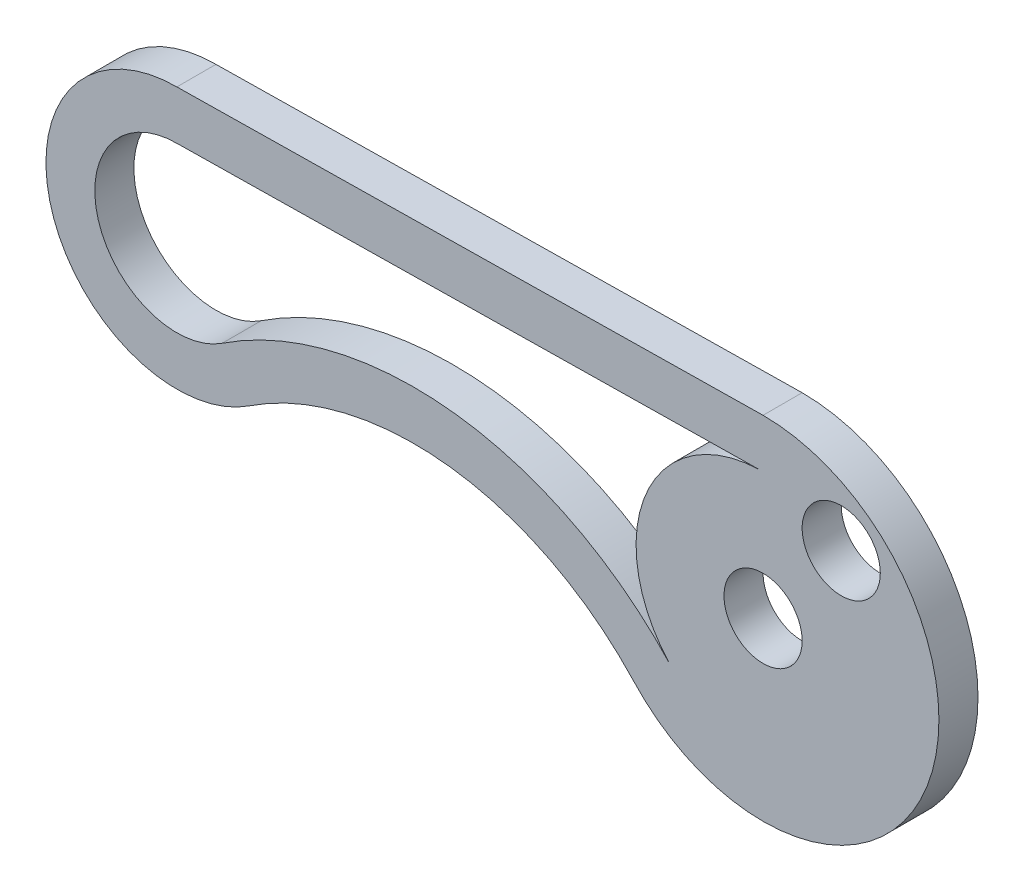
SolidWorks part; units mm, degrees
ref_plane "Front Plane" through (0, 0, 0) normal (0, 0, 1) x (1, 0, 0)
ref_plane "Top Plane" through (0, 0, 0) normal (0, 1, 0) x (1, 0, 0)
ref_plane "Right Plane" through (0, 0, 0) normal (1, 0, 0) x (0, 0, -1)
sketch "Sketch1" plane through (0, 0, 0) normal (0, 0, 1) x (1, 0, 0)
  line L0 (-31.0207, 8.8289) -> (-1.0207, 9.2757)
  line L1 (-31.0042, 6.3289) -> (-1.2314, 6.7723)
  line L3 (-31.0042, 6.3289) -> (-0.9835, 6.776) construction
  arc A0 (-31.0207, 8.8289) -> (-27.3206, -3.4568) centre (-31.0207, 2.1289) ccw
  arc A1 (-7.632, -5.8309) -> (-1.2887, 9.2717) centre (-1.0207, 0.2757) ccw
  arc A2 (-7.632, -5.8309) -> (-27.3206, -3.4568) centre (-18.8713, -16.2121) ccw
  circle A4 centre (-1.0207, 0.2757) radius 2
  circle A5 centre (2.9793, 5.2757) radius 2
  arc A6 (2.1739, 3.4451) -> (1.3701, 4.0881) centre (-1.0207, 0.2757) ccw
  arc A8 (-5.7955, -4.1346) -> (-28.7013, -1.3726) centre (-18.8713, -16.2121) ccw
  arc A9 (-31.0042, 6.3289) -> (-28.7013, -1.3726) centre (-31.0207, 2.1289) ccw
  circle A11 centre (-1.0207, 0.2757) radius 4.5 construction
  arc A13 (-5.7955, -4.1346) -> (-1.2143, 6.7728) centre (-1.0207, 0.2757) ccw construction
  arc A14 (-1.2314, 6.7723) -> (-5.7955, -4.1346) centre (-1.0207, 0.2757) ccw
  point P22 (3.4793, 0.2757)
  dimension "D1" = 30
  dimension "D2" = 18
  dimension "D3" = 13.4
  dimension "D6" = 4
  dimension "D7" = 4
  dimension "D9" = 2.5
  dimension "D4" = 4
  dimension "D8" = 5
extrude "Boss-Extrude1" add sketch "Sketch1" along normal blind 2
